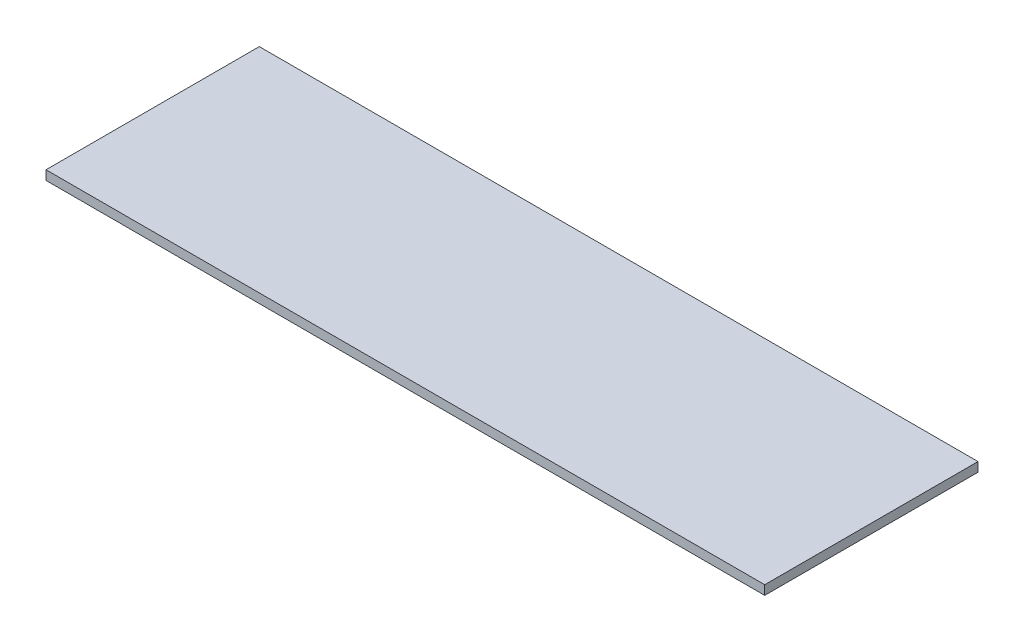
SolidWorks part; units mm, degrees
ref_plane "Front Plane" through (0, 0, 0) normal (0, 0, 1) x (1, 0, 0)
ref_plane "Top Plane" through (0, 0, 0) normal (0, 1, 0) x (1, 0, 0)
ref_plane "Right Plane" through (0, 0, 0) normal (1, 0, 0) x (0, 0, -1)
sketch "Sketch1" plane through (0, 0, 0) normal (0, 1, 0) x (1, 0, 0)
  line L1 (-77.5, -23) -> (77.5, -23)
  line L2 (-77.5, -23) -> (-77.5, 23)
  line L3 (-77.5, 23) -> (77.5, 23)
  line L4 (77.5, -23) -> (77.5, 23)
  line L5 (-77.5, -23) -> (77.5, 23) construction
  line L6 (-77.5, 23) -> (77.5, -23) construction
  point P0 (0, 0)
  dimension "D1" = 155
  dimension "D2" = 46
extrude "Boss-Extrude1" add sketch "Sketch1" along normal blind 2
